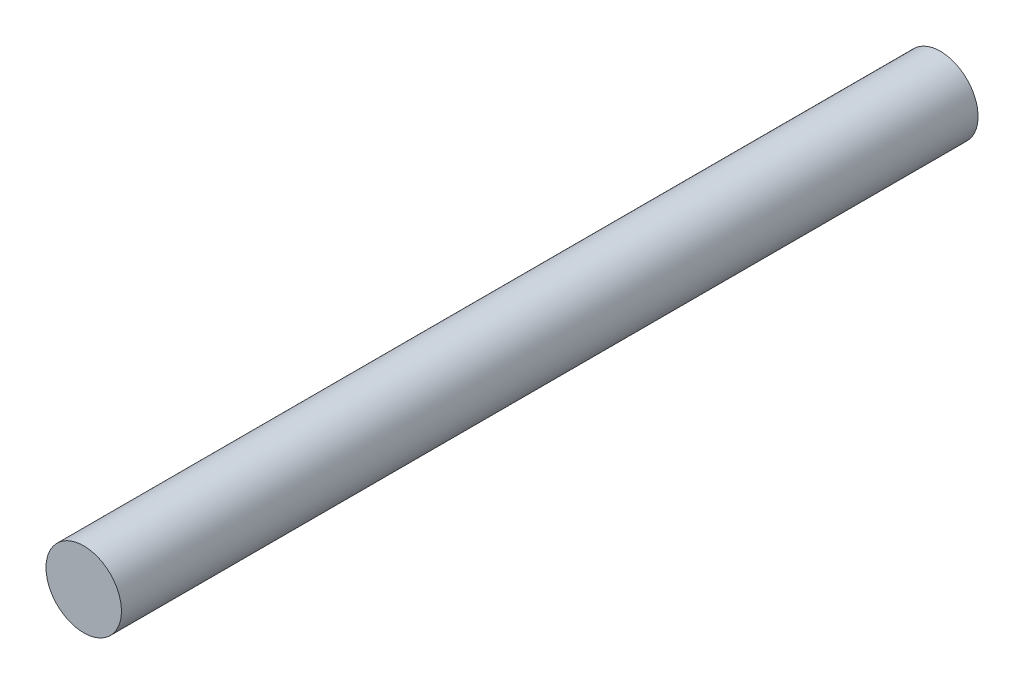
SolidWorks part; units mm, degrees
ref_plane "前视基准面" through (0, 0, 0) normal (0, 0, 1) x (1, 0, 0)
ref_plane "上视基准面" through (0, 0, 0) normal (0, 1, 0) x (1, 0, 0)
ref_plane "右视基准面" through (0, 0, 0) normal (1, 0, 0) x (0, 0, -1)
sketch "草图1" plane through (0, 0, 0) normal (0, 0, 1) x (1, 0, 0)
  circle A0 centre (0, 0) radius 3.5
  dimension "D1" = 7
extrude "凸台-拉伸1" add sketch "草图1" along normal blind 79.5
